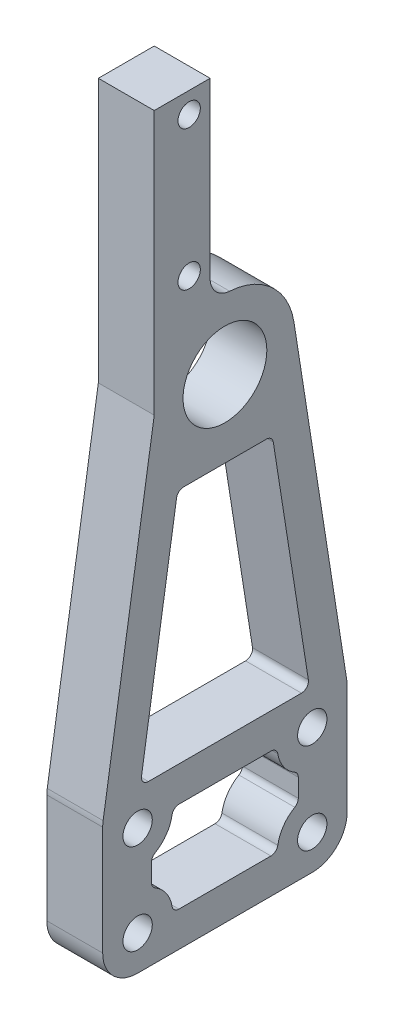
SolidWorks part; units mm, degrees
material "Thornel Mat VMA"
ref_plane "前视基准面" through (0, 0, 0) normal (0, 0, 1) x (1, 0, 0)
ref_plane "上视基准面" through (0, 0, 0) normal (0, 1, 0) x (1, 0, 0)
ref_plane "右视基准面" through (0, 0, 0) normal (1, 0, 0) x (0, 0, -1)
sketch "草图1" plane through (0, 0, 0) normal (1, 0, 0) x (0, 0, -1)
  line L0 (-17.5, -47) -> (-17.5, -68)
  line L1 (-12.5, -50) -> (12.5, -50) construction
  line L2 (-12.5, -50) -> (-12.5, -63) construction
  line L3 (-12.5, -63) -> (12.5, -63) construction
  line L4 (12.5, -50) -> (12.5, -63) construction
  line L5 (-17.5, -68) -> (17.5, -68)
  line L6 (17.5, -68) -> (17.5, -47)
  line L8 (-17.5, -47) -> (-10.1224, 0)
  line L9 (17.5, -47) -> (9.879, 1.5507)
  line L10 (-10.1224, 0) -> (-10.1224, 37.7722)
  line L17 (-10.1224, 37.7722) -> (-2.1224, 37.7722)
  line L18 (-2.1224, 37.7722) -> (-2.1224, 12.9703)
  line L19 (-5.1224, 34.7722) -> (-5.1224, 14.7722) construction
  circle A0 centre (0, 0) radius 6
  circle A1 centre (-12.5, -50) radius 2.1
  circle A2 centre (12.5, -50) radius 2.1
  circle A3 centre (-12.5, -63) radius 2.1
  circle A4 centre (12.5, -63) radius 2.1
  arc A5 (0.675, 9.9772) -> (9.879, 1.5507) centre (0, 0) cw
  circle A6 centre (-5.1224, 34.7722) radius 1.6
  circle A7 centre (-5.1224, 14.7722) radius 1.6
  arc A8 (-2.1224, 12.9703) -> (0.675, 9.9772) centre (0.8776, 12.9703) ccw
  point P10 (0, -50)
  point P29 (-2.1224, 9.7722)
  dimension "D1" = 12
  dimension "D4" = 4.2
  dimension "D9" = 10
  dimension "D12" = 3
  dimension "D13" = 3.2
  dimension "D17" = 3
  dimension "D2" = 13
  dimension "D3" = 25
  dimension "D5" = 50
  dimension "D6" = 5
  dimension "D7" = 5
  dimension "D8" = 5
  dimension "D10" = 28
  dimension "D11" = 3
  dimension "D14" = 3
  dimension "D15" = 20
  dimension "D16" = 8
extrude "凸台-拉伸1" add sketch "草图1" along normal blind 8
sketch "草图3" plane through (8, 0, 0) normal (1, 0, 0) x (0, 0, -1)
  line L15 (-6.9205, -11.8449) -> (-11.9435, -43.8449)
  line L16 (-10.9556, -45) -> (10.9556, -45)
  line L17 (11.9435, -43.8449) -> (6.9205, -11.8449)
  line L18 (5.9326, -11) -> (-5.9326, -11)
  line L19 (-10.1224, 0) -> (-17.5, -47) construction
  line L20 (17.5, -47) -> (9.879, 1.5507) construction
  line L21 (-10.5, -55.1962) -> (-10.5, -57.8038)
  line L22 (-6.5839, -50) -> (6.5839, -50)
  line L23 (10.5, -55.1962) -> (10.5, -57.8038)
  line L24 (6.5839, -63) -> (-6.5839, -63)
  circle A0 centre (12.5, -50) radius 2.1 construction
  arc A1 (-7.5699, -50.8333) -> (-10, -54.3301) centre (-12.5, -50) cw
  arc A2 (7.5699, -50.8333) -> (10, -54.3301) centre (12.5, -50) ccw
  arc A3 (10, -58.6699) -> (7.5699, -62.1667) centre (12.5, -63) ccw
  arc A4 (-10, -58.6699) -> (-7.5699, -62.1667) centre (-12.5, -63) cw
  circle A5 centre (-12.5, -50) radius 2.1 construction
  arc A6 (7.5699, -50.8333) -> (6.5839, -50) centre (6.5839, -51) ccw
  arc A7 (10, -54.3301) -> (10.5, -55.1962) centre (9.5, -55.1962) cw
  arc A8 (10, -58.6699) -> (10.5, -57.8038) centre (9.5, -57.8038) ccw
  arc A9 (7.5699, -62.1667) -> (6.5839, -63) centre (6.5839, -62) cw
  arc A10 (-7.5699, -62.1667) -> (-6.5839, -63) centre (-6.5839, -62) ccw
  arc A11 (-10, -58.6699) -> (-10.5, -57.8038) centre (-9.5, -57.8038) cw
  arc A12 (-10, -54.3301) -> (-10.5, -55.1962) centre (-9.5, -55.1962) ccw
  arc A13 (-7.5699, -50.8333) -> (-6.5839, -50) centre (-6.5839, -51) cw
  arc A20 (-6.9205, -11.8449) -> (-5.9326, -11) centre (-5.9326, -12) cw
  arc A21 (6.9205, -11.8449) -> (5.9326, -11) centre (5.9326, -12) ccw
  arc A22 (10.9556, -45) -> (11.9435, -43.8449) centre (10.9556, -44) ccw
  arc A23 (-11.9435, -43.8449) -> (-10.9556, -45) centre (-10.9556, -44) ccw
  dimension "D12" = 5
  dimension "D15" = 1
  dimension "D2" = 1
  dimension "D3" = 11
  dimension "D9" = 5
  dimension "D10" = 5
  dimension "D11" = 5
  dimension "D13" = 2
  dimension "D14" = 2
extrude "切除-拉伸2" cut sketch "草图3" against normal through all
fillet "圆角1" radius 5 4 edges at (4, -47, 17.5) (4, -47, -17.5) (4, -68, -17.5) (4, -68, 17.5)
